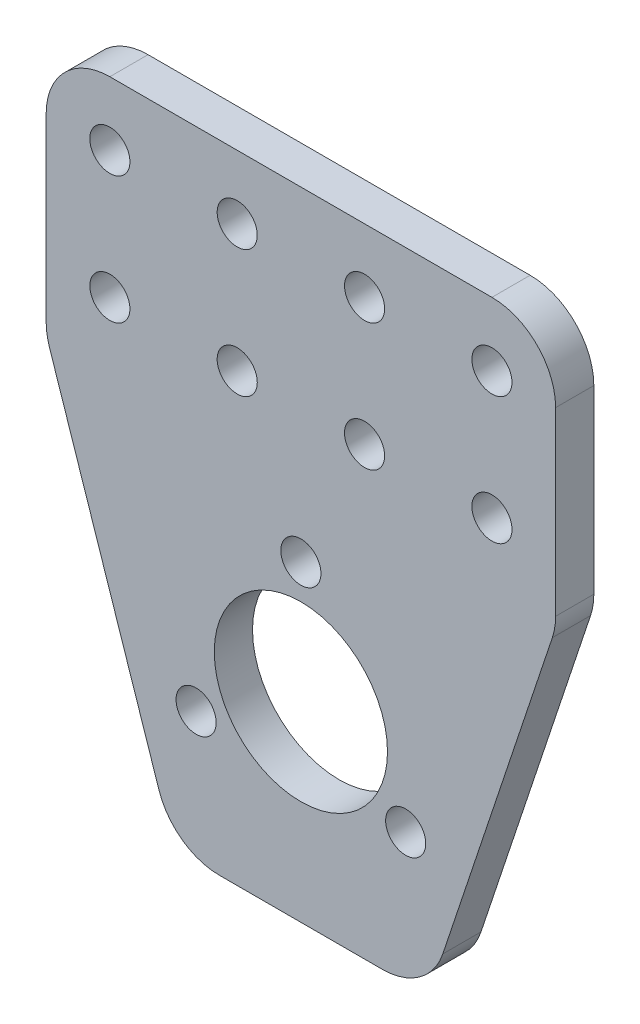
SolidWorks part; units mm, degrees
ref_plane "前视基准面" through (0, 0, 0) normal (0, 0, 1) x (1, 0, 0)
ref_plane "上视基准面" through (0, 0, 0) normal (0, 1, 0) x (1, 0, 0)
ref_plane "右视基准面" through (0, 0, 0) normal (1, 0, 0) x (0, 0, -1)
other "Configuration Table"
sketch "草图1" plane through (0, 0, 0) normal (0, 0, 1) x (1, 0, 0)
  line L0 (0, 0) -> (0, -20)
  line L4 (40, -20) -> (40, 0)
  line L5 (40, 0) -> (0, 0)
  line L6 (20, 0) -> (20, -50) construction
  line L7 (40, -20) -> (30, -50)
  line L8 (0, -20) -> (10, -50)
  line L9 (30, -50) -> (10, -50)
  dimension "D1" = 20
  dimension "D2" = 40
  dimension "D3" = 20
  dimension "D4" = 50
extrude "凸台-拉伸1" add sketch "草图1" along normal blind 3
sketch "草图2" plane through (0, 0, 3) normal (0, 0, 1) x (1, 0, 0)
  line L0 (0, -10) -> (40, -10) construction
  line L1 (0, 0) -> (0, -20) construction
  line L2 (40, -20) -> (40, 0) construction
  line L3 (20, 0) -> (20, -50) construction
  line L4 (40, 0) -> (0, 0) construction
  line L5 (10, 0) -> (10, -10) construction
  line L6 (10, -50) -> (30, -50) construction
  circle A0 centre (5, -5) radius 1.575
  circle A1 centre (15, -5) radius 1.575
  circle A2 centre (15, -15) radius 1.575
  circle A3 centre (5, -15) radius 1.575
  circle A4 centre (35, -15) radius 1.575
  circle A5 centre (25, -15) radius 1.575
  circle A6 centre (25, -5) radius 1.575
  circle A7 centre (35, -5) radius 1.575
  circle A8 centre (20, -35) radius 6.8
  circle A9 centre (20, -25.5) radius 1.575
  circle A10 centre (28.2272, -39.75) radius 1.575
  circle A11 centre (11.7728, -39.75) radius 1.575
  point P40 (20, -35)
  dimension "D1" = 3.15
  dimension "D5" = 13.6
  dimension "D8" = 3.15
  dimension "D2" = 5
  dimension "D3" = 5
  dimension "D4" = 10
  dimension "D6" = 15
  dimension "D7" = 9.5
  dimension "D9" = 3
extrude "切除-拉伸2" cut sketch "草图2" against normal through all
fillet "圆角1" radius 5 6 edges at (30, -50, 1.5) (10, -50, 1.5) (0, -20, 1.5) (40, -20, 1.5) (40, 0, 1.5) (0, 0, 1.5)
